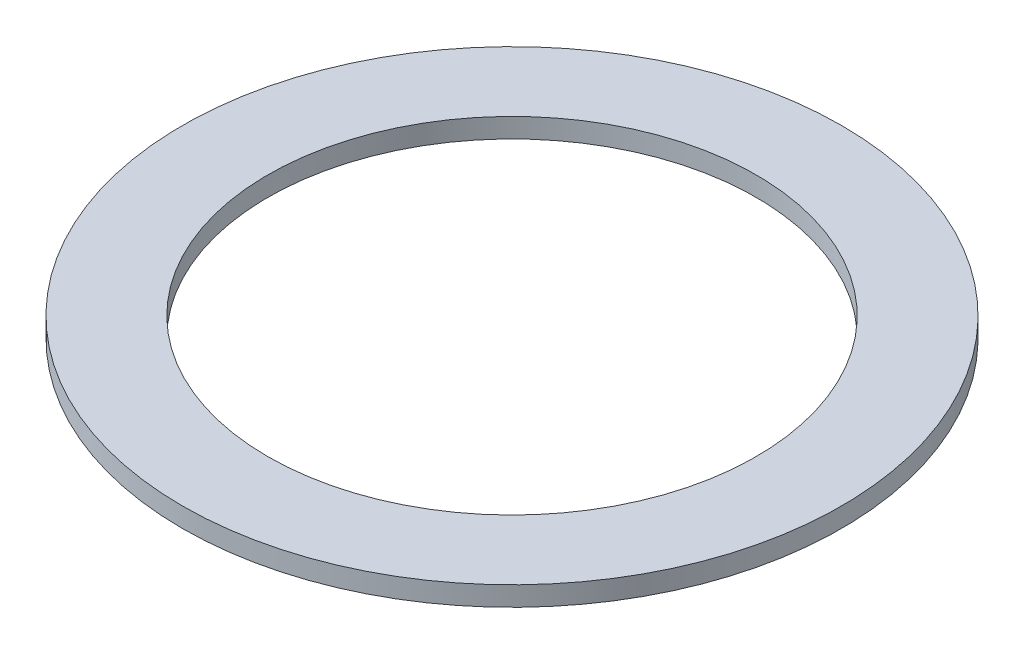
SolidWorks part; units mm, degrees
ref_plane "Front Plane" through (0, 0, 0) normal (0, 0, 1) x (1, 0, 0)
ref_plane "Top Plane" through (0, 0, 0) normal (0, 1, 0) x (1, 0, 0)
ref_plane "Right Plane" through (0, 0, 0) normal (1, 0, 0) x (0, 0, -1)
sketch "Sketch1" plane through (0, 0, 0) normal (0, 1, 0) x (1, 0, 0)
  circle A0 centre (0, 0) radius 50
  circle A1 centre (0, 0) radius 67.5
  dimension "D1" = 100
  dimension "D2" = 135
extrude "Boss-Extrude1" add sketch "Sketch1" along normal blind 4
